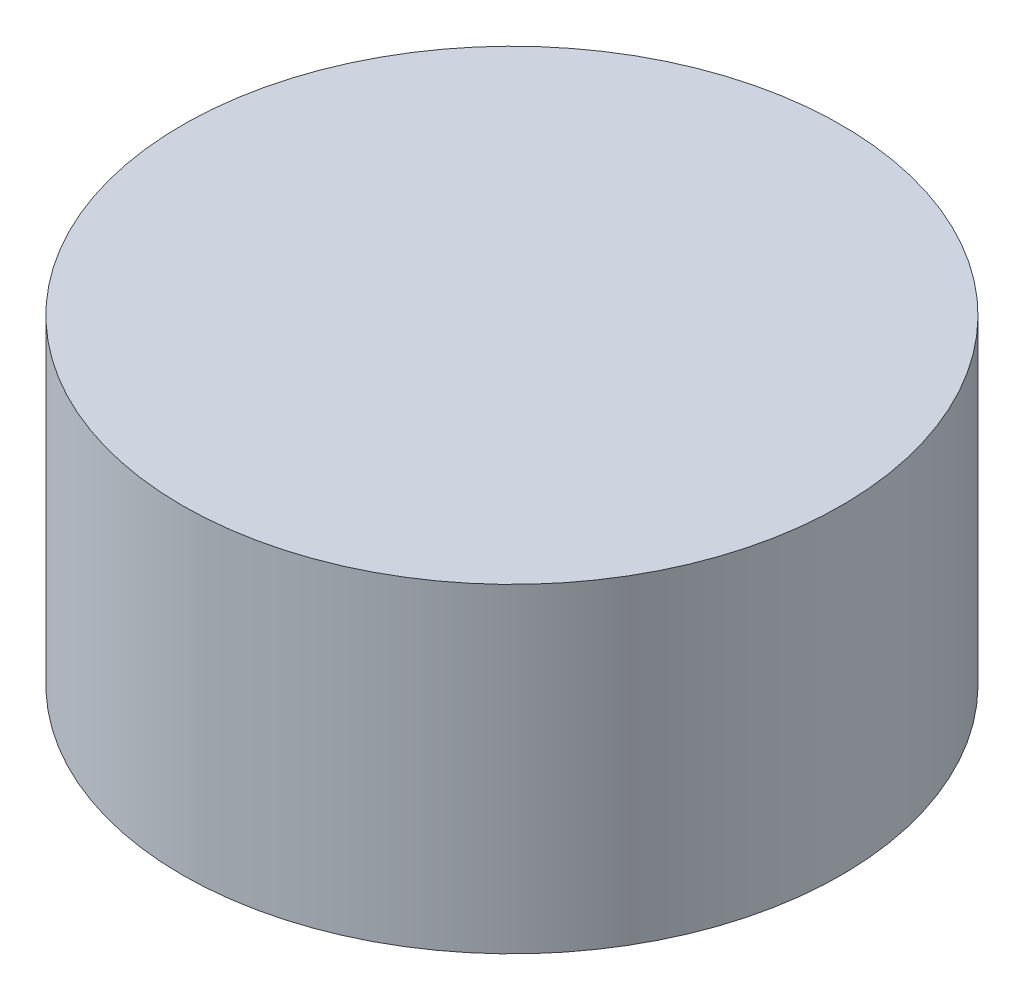
SolidWorks part; units mm, degrees
material "Argent pur"
ref_plane "Plan de face" through (0, 0, 0) normal (0, 0, 1) x (1, 0, 0)
ref_plane "Plan de dessus" through (0, 0, 0) normal (0, 1, 0) x (1, 0, 0)
ref_plane "Plan de droite" through (0, 0, 0) normal (1, 0, 0) x (0, 0, -1)
sketch "Esquisse1" plane through (0, 0, 0) normal (0, 1, 0) x (1, 0, 0)
  circle A0 centre (0, 0) radius 30.9
  dimension "D1" = 30.9
extrude "Boss.-Extru.1" add sketch "Esquisse1" along normal blind 30
sketch "Esquisse2" plane through (0, 0, 0) normal (0, 1, 0) x (1, 0, 0)
  line L0 (-30.9, 22.2465) -> (-30.9, -23.4753)
  circle A0 centre (0, 0) radius 30.9 construction
equation "\"r1\"=30.9"
equation "\"D1@Esquisse1\"=\"r1\""
equation "\"h1\"=30"
equation "\"D1@Boss.-Extru.1\"=\"h1\""
